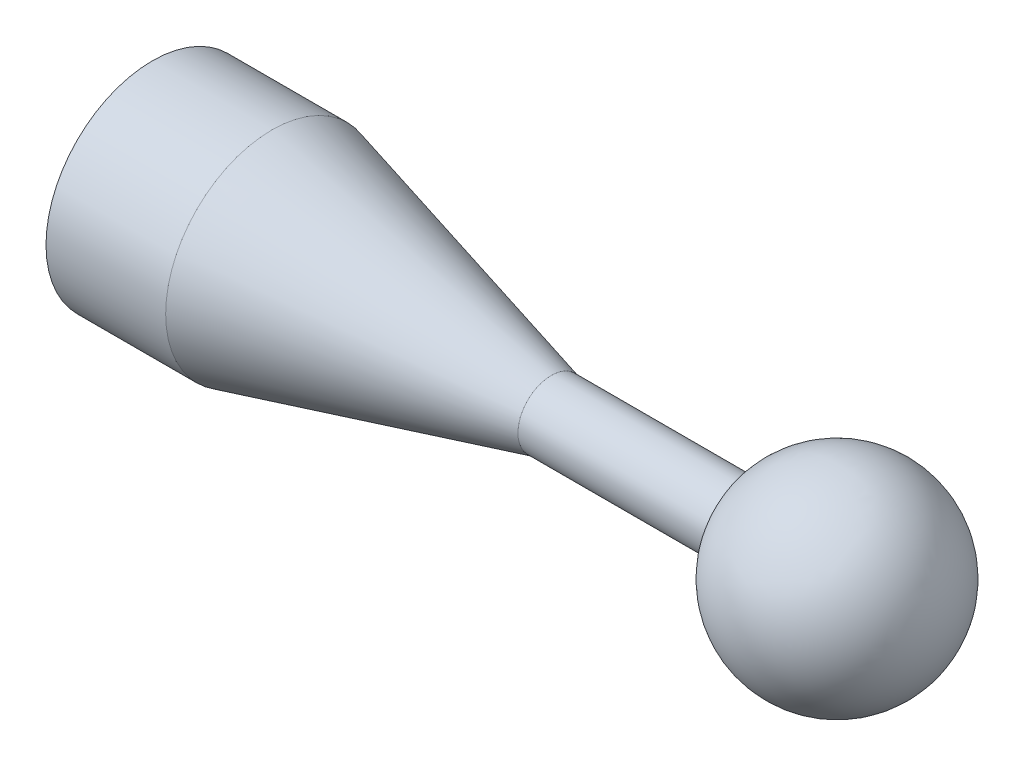
SolidWorks part; units mm, degrees
material "3.0205 (EN-AW 1200)"
ref_plane "Plan de face" through (0, 0, 0) normal (0, 0, 1) x (1, 0, 0)
ref_plane "Plan de dessus" through (0, 0, 0) normal (0, 1, 0) x (1, 0, 0)
ref_plane "Plan de droite" through (0, 0, 0) normal (1, 0, 0) x (0, 0, -1)
sketch "Esquisse1" plane through (0, 0, 0) normal (0, 0, 1) x (1, 0, 0)
  line L0 (0, 0) -> (0, 16)
  line L1 (0, 16) -> (18, 16)
  line L2 (18, 16) -> (60, 5)
  line L3 (60, 5) -> (88.8579, 5)
  line L4 (-11.8977, 0) -> (129.4239, 0) construction
  line L5 (0, 0) -> (118, 0)
  arc A0 (118, 0) -> (88.8579, 5) centre (103, 0) ccw
  dimension "D6" = 15
  dimension "D1" = 16
  dimension "D2" = 18
  dimension "D3" = 42
  dimension "D4" = 5
  dimension "D5" = 103
revolve "Révolution1" add sketch "Esquisse1" angle 360 about L4
ref_point "Point1"
